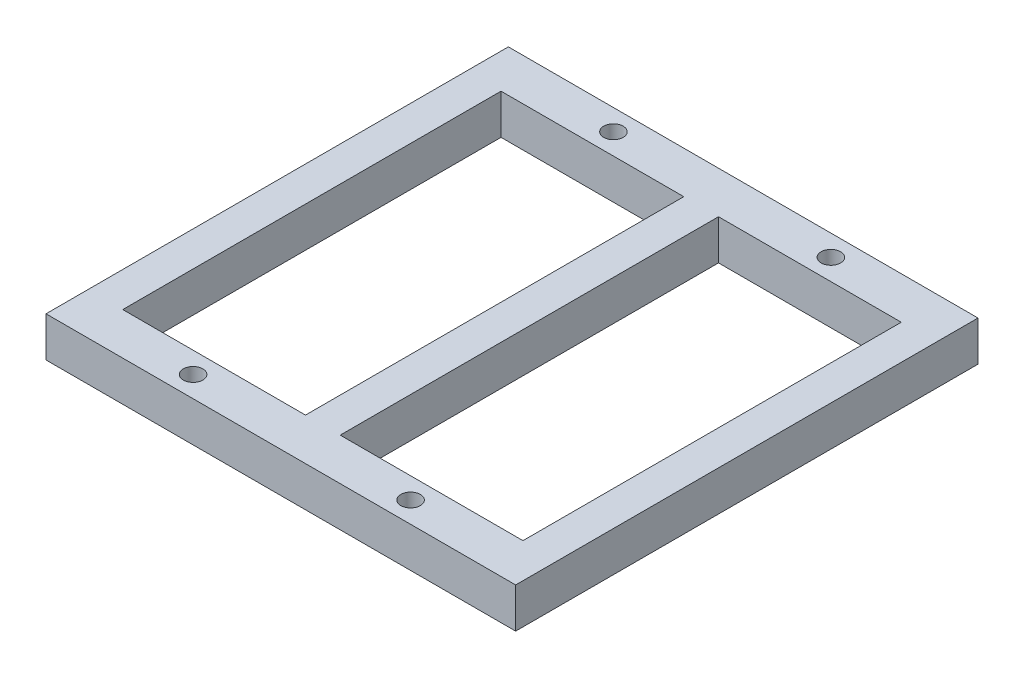
SolidWorks part; units mm, degrees
ref_plane "Front Plane" through (0, 0, 0) normal (0, 0, 1) x (1, 0, 0)
ref_plane "Top Plane" through (0, 0, 0) normal (0, 1, 0) x (1, 0, 0)
ref_plane "Right Plane" through (0, 0, 0) normal (1, 0, 0) x (0, 0, -1)
sketch "Sketch2" plane through (0, 0, 0) normal (0, 1, 0) x (1, 0, 0)
  line L0 (0, 34.925) -> (0, -34.925) construction
  line L1 (-19.05, 34.925) -> (19.05, 34.925)
  line L2 (-19.05, 34.925) -> (-19.05, -34.925) construction
  line L3 (-19.05, -34.925) -> (19.05, -34.925)
  line L4 (19.05, 34.925) -> (19.05, -34.925)
  line L5 (-19.05, 0) -> (19.05, 0) construction
  line L6 (-19.05, 34.925) -> (-51.9049, 34.925)
  line L7 (-13.8049, 28.575) -> (13.8049, 28.575)
  line L8 (-13.8049, 28.575) -> (-13.8049, -28.575)
  line L9 (-13.8049, -28.575) -> (13.8049, -28.575)
  line L10 (13.8049, 28.575) -> (13.8049, -28.575)
  line L11 (-13.8049, 28.575) -> (13.8049, -28.575) construction
  line L12 (-13.8049, -28.575) -> (13.8049, 28.575) construction
  line L13 (-51.9049, 34.925) -> (-51.9049, -34.925)
  line L14 (-51.9049, -34.925) -> (-19.05, -34.925)
  line L15 (-32.8549, 34.925) -> (-32.8549, -34.925) construction
  line L16 (-46.6598, 28.575) -> (-19.05, 28.575)
  line L17 (-46.6598, 28.575) -> (-46.6598, -28.575)
  line L18 (-46.6598, -28.575) -> (-19.05, -28.575)
  line L19 (-19.05, 28.575) -> (-19.05, -28.575)
  line L20 (-46.6598, 28.575) -> (-19.05, -28.575) construction
  line L21 (-46.6598, -28.575) -> (-19.05, 28.575) construction
  line L22 (-46.6598, 0) -> (-19.05, 0) construction
  circle A0 centre (0, 31.75) radius 1.4732
  circle A1 centre (-32.8549, 31.75) radius 1.4732
  circle A2 centre (0, -31.75) radius 1.4732
  circle A3 centre (-32.8549, -31.75) radius 1.4732
  point P0 (0, 0)
  point P15 (-32.8549, 0)
  point P22 (-17.4169, 28.575)
  dimension "D3" = 27.6098
  dimension "D6" = 38.1
  dimension "D4" = 3.175
  dimension "D1" = 69.85
  dimension "D5" = 2.9464
  dimension "D2" = 57.15
  dimension "D7" = 32.8549
  dimension "D8" = 32.8549
extrude "Boss-Extrude1" add sketch "Sketch2" along normal blind 6.0452
